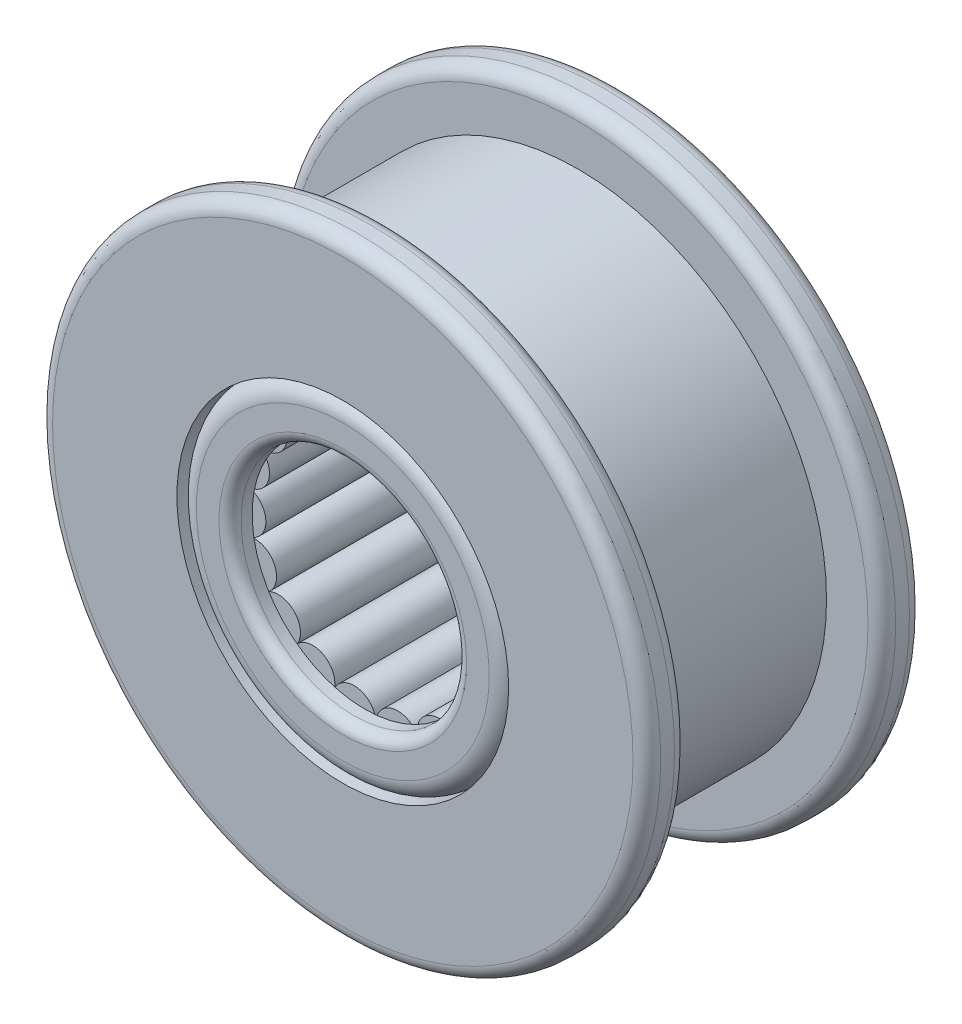
SolidWorks part; units mm, degrees
ref_plane "Front Plane" through (0, 0, 0) normal (0, 0, 1) x (1, 0, 0)
ref_plane "Top Plane" through (0, 0, 0) normal (0, 1, 0) x (1, 0, 0)
ref_plane "Right Plane" through (0, 0, 0) normal (1, 0, 0) x (0, 0, -1)
sketch "Sketch1" plane through (0, 0, 0) normal (1, 0, 0) x (0, 0, -1)
  line L0 (0, 0) -> (15.875, 0) construction
  line L1 (13.4937, 17.4625) -> (15.875, 17.4625)
  line L2 (0, 9.525) -> (15.875, 9.525)
  line L4 (0, 17.4625) -> (2.3812, 17.4625)
  line L5 (15.875, 9.525) -> (15.875, 17.4625)
  line L7 (2.3812, 17.4625) -> (2.3812, 14.2875)
  line L8 (2.3812, 14.2875) -> (13.4937, 14.2875)
  line L9 (13.4937, 17.4625) -> (13.4937, 14.2875)
  line L12 (0, 9.525) -> (0, 6.35) construction
  line L13 (0, 9.525) -> (0, 17.4625)
  line L15 (15.875, 9.525) -> (15.875, 6.35) construction
  line L16 (15.875, 6.35) -> (0, 6.35) construction
  dimension "D1" = 3.175
  dimension "A" = 34.925
  dimension "B" = 15.875
  dimension "C" = 12.7
  dimension "D" = 28.575
  dimension "E" = 11.1125
  dimension "G" = 15.875
  dimension "I" = 0
  dimension "F" = 0
revolve "Revolve1" add sketch "Sketch1" angle 360 about L0
fillet "Fillet1" radius 0.795 4 edges at (17.4625, 0, -15.875) (17.4625, 0, -13.4937) (17.4625, 0, -2.3812) (17.4625, 0, 0)
sketch "Sketch2" plane through (0, 0, 0) normal (1, 0, 0) x (0, 0, -1)
  line L0 (0, 0) -> (15.875, 0) construction
  line L1 (0, 6.477) -> (1.27, 6.477)
  line L2 (0, 6.477) -> (0, 9.525)
  line L3 (0, 9.525) -> (15.875, 9.525)
  line L4 (15.875, 6.477) -> (15.875, 9.525)
  line L6 (15.875, 6.35) -> (0, 6.35) construction
  line L7 (1.27, 6.477) -> (1.27, 8.255)
  line L8 (1.27, 8.255) -> (14.605, 8.255)
  line L9 (14.605, 8.255) -> (14.605, 6.477)
  line L10 (14.605, 6.477) -> (15.875, 6.477)
  line L11 (1.27, 8.255) -> (1.27, 9.525) construction
  dimension "D1" = 0.127
  dimension "D2" = 1.27
revolve "Revolve2" add sketch "Sketch2" angle 360 about L0
fillet "Fillet2" radius 1.1125 2 edges at (0, -9.525, 0) (0, -9.525, -15.875)
fillet "Fillet3" radius 0.635 2 edges at (0, -6.477, 0) (0, -6.477, -15.875)
sketch "Sketch3" plane through (0, 0, -1.27) normal (0, 0, 1) x (1, 0, 0)
  line L0 (0, 0) -> (-1.2522, 7.4083) construction
  line L1 (0, 0) -> (1.2522, 7.4083) construction
  circle A0 centre (0, 7.62) radius 1.27
  circle A1 centre (0, 0) radius 6.35 construction
  dimension "D1" = 2.54
  dimension "D2" = 19.188
extrude "Boss-Extrude1" add sketch "Sketch3" against normal offset from surface (12.065 mm away) 0.635 from offset 0.635 separate body up to face at (0, -6.477, -14.605) offset against normal yes
pattern_circular "CirPattern1" count 19 over 360 about axis through (0, 0, 0) along (0, 0, 1) of bodies 104
equation "\"D1@CirPattern1\" = \"D3@CirPattern1\" / \"D2@Sketch3\""
